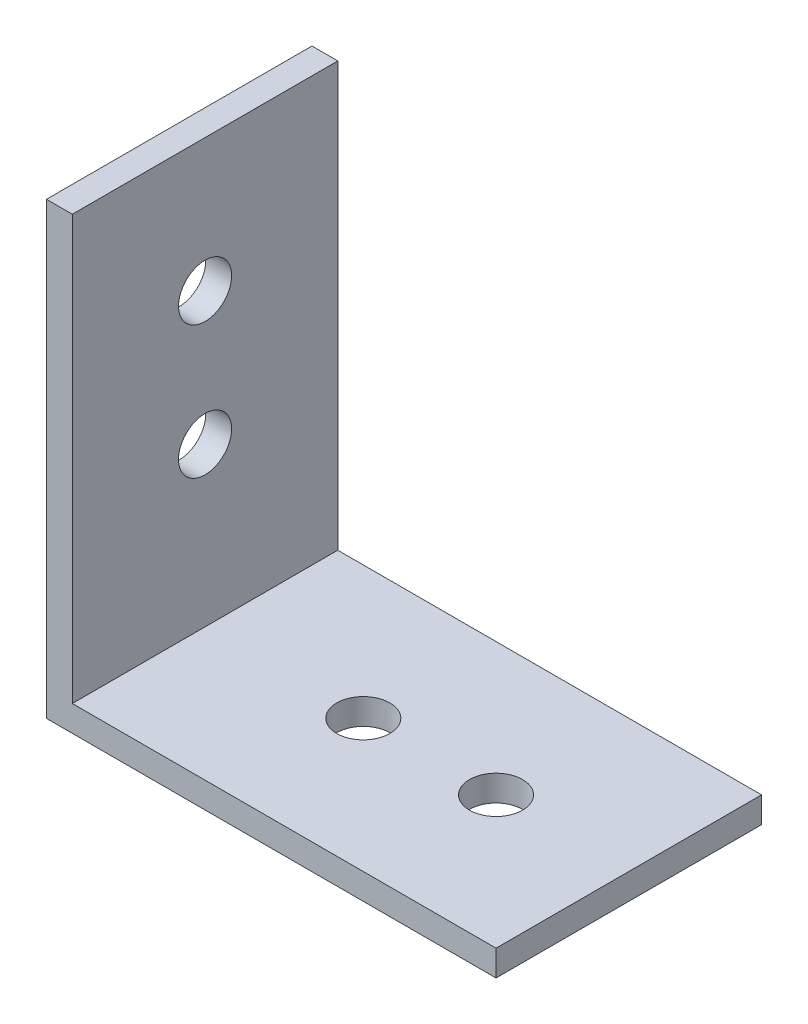
SolidWorks part; units mm, degrees
ref_plane "Front Plane" through (0, 0, 0) normal (0, 0, 1) x (1, 0, 0)
ref_plane "Top Plane" through (0, 0, 0) normal (0, 1, 0) x (1, 0, 0)
ref_plane "Right Plane" through (0, 0, 0) normal (1, 0, 0) x (0, 0, -1)
sketch "Sketch1" plane through (0, 0, 0) normal (1, 0, 0) x (0, 0, -1)
  line L1 (0, 0) -> (15, 0)
  line L2 (0, 0) -> (0, 25.4)
  line L3 (0, 25.4) -> (15, 25.4)
  line L4 (15, 0) -> (15, 25.4)
  dimension "D1" = 25.4
  dimension "D2" = 15
extrude "Boss-Extrude1" add sketch "Sketch1" along normal blind 3.175
sketch "Sketch2" plane through (3.175, 0, 0) normal (1, 0, 0) x (0, 0, -1)
  line L0 (15, 0) -> (15, 25.4) construction
  line L1 (0, 0) -> (15, 0)
  line L2 (0, 0) -> (0, 3.175)
  line L3 (0, 3.175) -> (15, 3.175)
  line L4 (15, 0) -> (15, 3.175)
  dimension "D1" = 3.175
extrude "Boss-Extrude2" add sketch "Sketch2" along normal blind 22.225
sketch "Sketch3" plane through (0, 0, 0) normal (0, -1, 0) x (1, 0, 0)
  circle A2 centre (10.4, -7.5) radius 1.5
  circle A3 centre (17.9, -7.5) radius 1.5
sketch "Sketch4" plane through (3.175, 0, 0) normal (1, 0, 0) x (0, 0, -1)
  line L0 (7.5, 25.4) -> (7.5, 10.4)
  line L1 (15, 25.4) -> (0, 25.4) construction
  circle A0 centre (7.5, 17.9) radius 1.5
  circle A1 centre (7.5, 10.4) radius 1.5
  dimension "D1" = 15
extrude "Cut-Extrude3" cut sketch "Sketch4" against normal through all contours A0 | A1
extrude "Cut-Extrude4" cut sketch "Sketch3" against normal through all
sketch "Sketch7" plane through (0, 3.175, 0) normal (0, 1, 0) x (1, 0, 0)
  line L1 (3.175, 0) -> (25.4, 0)
  line L2 (3.175, 0) -> (3.175, 15)
  line L3 (3.175, 15) -> (25.4, 15)
  line L4 (25.4, 0) -> (25.4, 15)
extrude "Cut-Extrude7" cut sketch "Sketch7" against normal blind 1.7145
sketch "Sketch8" plane through (3.175, 0, 0) normal (1, 0, 0) x (0, 0, -1)
  line L1 (0, 25.4) -> (15, 25.4)
  line L2 (0, 25.4) -> (0, 1.4605)
  line L3 (0, 1.4605) -> (15, 1.4605)
  line L4 (15, 25.4) -> (15, 1.4605)
extrude "Cut-Extrude8" cut sketch "Sketch8" against normal blind 1.7145
